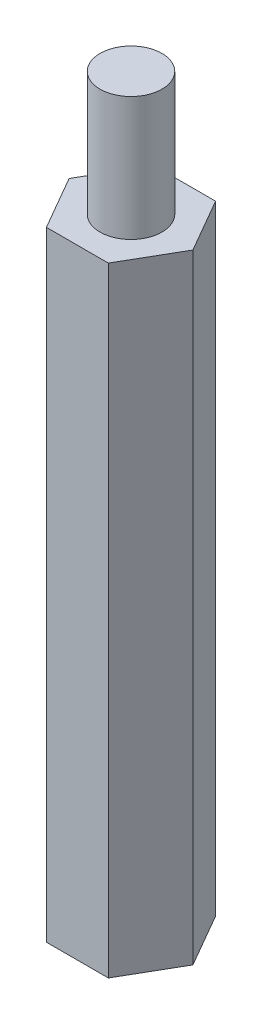
SolidWorks part; units mm, degrees
ref_plane "前视基准面" through (0, 0, 0) normal (0, 0, 1) x (1, 0, 0)
ref_plane "上视基准面" through (0, 0, 0) normal (0, 1, 0) x (1, 0, 0)
ref_plane "右视基准面" through (0, 0, 0) normal (1, 0, 0) x (0, 0, -1)
sketch "草图1" plane through (0, 0, 0) normal (0, 1, 0) x (1, 0, 0)
  line L1 (1.5, 2.5981) -> (-1.5, 2.5981)
  line L2 (-1.5, 2.5981) -> (-3, 0)
  line L3 (-3, 0) -> (-1.5, -2.5981)
  line L4 (-1.5, -2.5981) -> (1.5, -2.5981)
  line L5 (1.5, -2.5981) -> (3, 0)
  line L6 (3, 0) -> (1.5, 2.5981)
  circle A0 centre (0, 0) radius 2.5981 construction
  dimension "D1" = 3
extrude "凸台-拉伸1" add sketch "草图1" along normal blind 30
hole_wizard "M3 螺纹孔1" positions "草图2" profile "草图3" tap size "M3" standard "GB" end condition through all
sketch "草图2" plane through (0, 30, 0) normal (0, 1, 0) x (1, 0, 0)
  point P0 (0, 0)
sketch "草图3" plane through (0, 30, 0) normal (1, 0, 0) x (0, 0, 1)
  line L0 (0, 0) -> (0, 30)
  line L1 (0, 30) -> (1.25, 30)
  line L2 (1.25, 30) -> (1.25, 0)
  line L5 (1.25, 0) -> (0, 0)
  line L11 (0, -6.35) -> (0, 107.95) construction
  dimension "通孔螺纹孔钻头直径" = 2.5
  dimension "通孔螺纹孔钻头深度" = 30
cosmetic thread "孔螺蚊线1" parameters "D2"=3
sketch "草图4" plane through (0, 30, 0) normal (0, 1, 0) x (1, 0, 0)
  circle A0 centre (0, 0) radius 1.5
  dimension "D1" = 3
extrude "凸台-拉伸3" add sketch "草图4" along normal blind 6 and the other way blind 5 from surface at 0 starting at face at (0, 30, 1.25)
